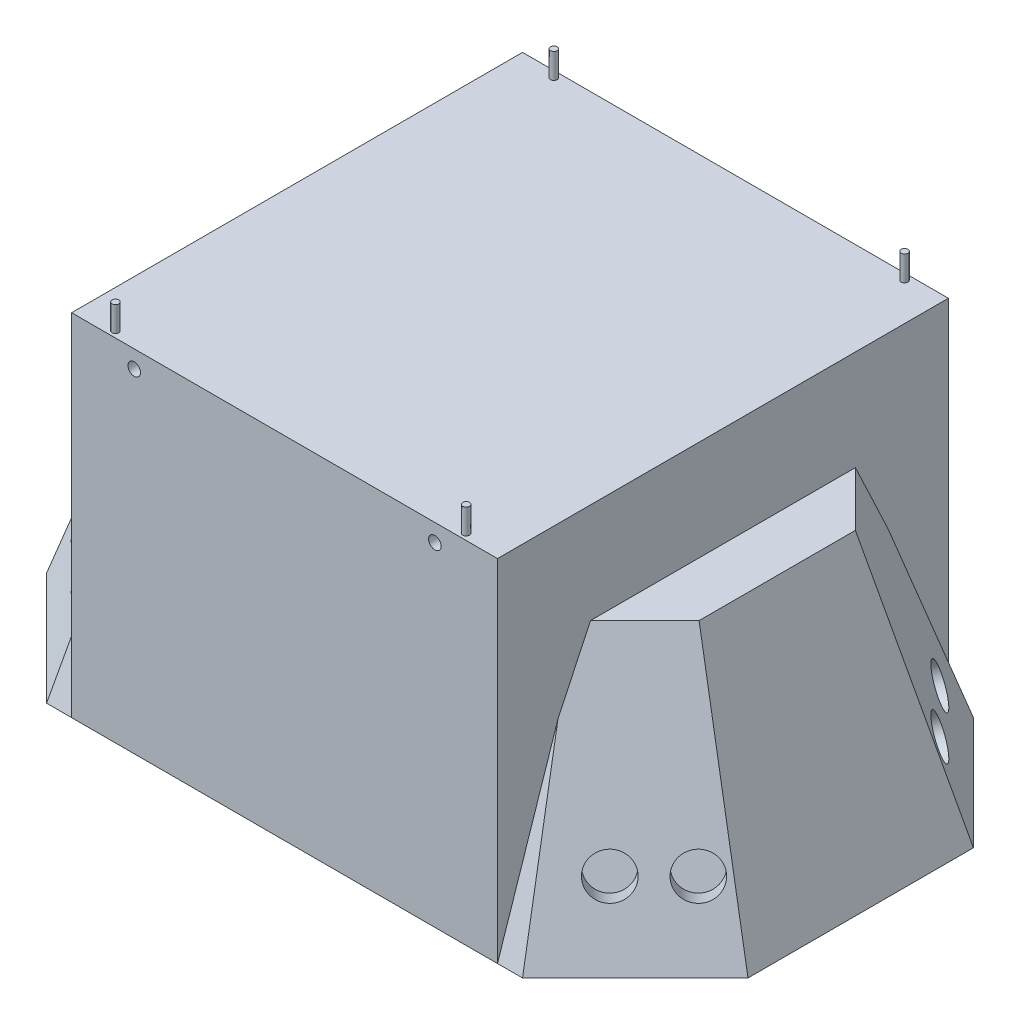
SolidWorks part; units mm, degrees
ref_plane "Front Plane" through (0, 0, 0) normal (0, 0, 1) x (1, 0, 0)
ref_plane "Top Plane" through (0, 0, 0) normal (0, 1, 0) x (1, 0, 0)
ref_plane "Right Plane" through (0, 0, 0) normal (1, 0, 0) x (0, 0, -1)
sketch "Sketch1" plane through (0, 0, 0) normal (0, 1, 0) x (1, 0, 0)
  line L0 (-140, -45) -> (-125, -60)
  line L1 (-125, -60) -> (-95, -90)
  line L2 (-95, -90) -> (95, -90)
  line L3 (95, -90) -> (140, -45)
  line L4 (140, -45) -> (140, 45)
  line L5 (140, 45) -> (95, 90)
  line L6 (95, 90) -> (-95, 90)
  line L7 (-95, 90) -> (-140, 45)
  line L8 (-140, 45) -> (-140, -45)
extrude "Boss-Extrude1" add sketch "Sketch1" along normal blind 100 draft 18.43
sketch "Sketch2" plane through (0, 0, 0) normal (0, 0, 1) x (1, 0, 0)
  line L0 (-85, 140) -> (85, 140)
  line L1 (85, 140) -> (85, -50)
  line L2 (85, -50) -> (-85, -50)
  line L3 (-85, -50) -> (-85, 140)
  line L4 (-81.1969, 100) -> (81.1969, 100) construction
  dimension "D1" = 40
  dimension "D2" = 85
  dimension "D3" = 190
  dimension "D4" = 170
extrude "Boss-Extrude2" add sketch "Sketch2" along normal mid plane 180
sketch "Sketch3" plane through (0, 140, 0) normal (0, 1, 0) x (1, 0, 0)
  line L0 (-85, -90) -> (-85, 90) construction
  line L1 (85, -90) -> (85, 90) construction
  line L2 (85, 90) -> (-85, 90) construction
  circle A0 centre (-70, 87.5) radius 1.35
  circle A1 centre (70, 87.5) radius 1.35
  point P8 (0, 0)
  point P11 (0, 0)
  dimension "D5" = 2.7
  dimension "D6" = 2.7
  dimension "D1" = 15
  dimension "D2" = 15
  dimension "D3" = 2.5
  dimension "D4" = 2.5
extrude "Boss-Extrude3" add sketch "Sketch3" along normal mid plane 20
mirror "Mirror1" about plane through (0, 0, 0) normal (0, 0, 1) of "Boss-Extrude3"
sketch "Sketch4" plane through (-85, 0, 0) normal (-1, 0, 0) x (0, 0, 1)
  line L1 (-90, 0) -> (90, 0)
  line L2 (-90, 0) -> (-90, -50)
  line L3 (-90, -50) -> (90, -50)
  line L4 (90, 0) -> (90, -50)
extrude "Cut-Extrude1" cut sketch "Sketch4" against normal through all
sketch "Sketch5" plane through (0, 0, -90) normal (0, 0, -1) x (-1, 0, 0)
  line L0 (-85, 140) -> (85, 140) construction
  line L1 (-85, 0) -> (-85, 140) construction
  line L2 (85, 140) -> (85, 0) construction
  circle A0 centre (-60, 133) radius 2.5
  circle A1 centre (60, 133) radius 2.5
  point P8 (0, 0)
  dimension "D5" = 5
  dimension "D6" = 5
  dimension "D1" = 7
  dimension "D2" = 7
  dimension "D3" = 25
  dimension "D4" = 25
extrude "Cut-Extrude2" cut sketch "Sketch5" against normal blind 10
mirror "Mirror2" about plane through (0, 0, 0) normal (0, 0, 1) of "Cut-Extrude2"
sketch "Sketch6" plane through (-83.2548, 39.2354, -83.2548) normal (-0.6708, 0.3161, -0.6708) x (-0.6068, 0.286, 0.7416)
  line L0 (-9.0954, -40.4986) -> (51.584, -59.6821) construction
  line L1 (70.1966, 44.9819) -> (51.584, -59.6821) construction
  circle A0 centre (23.428, -19.3172) radius 8
  circle A1 centre (47.2651, -26.8532) radius 8
  dimension "D5" = 16
  dimension "D6" = 16
  dimension "D1" = 30
  dimension "D2" = 30
  dimension "D3" = 25
  dimension "D4" = 10
extrude "Cut-Extrude3" cut sketch "Sketch6" against normal blind 10
mirror "Mirror3" about plane through (0, 0, 0) normal (0, 0, 1) of "Cut-Extrude3"
mirror "Mirror4" about plane through (0, 0, 0) normal (1, 0, 0) of "Mirror3", "Cut-Extrude3"
equation "\"18.43.00deg\"=20"
